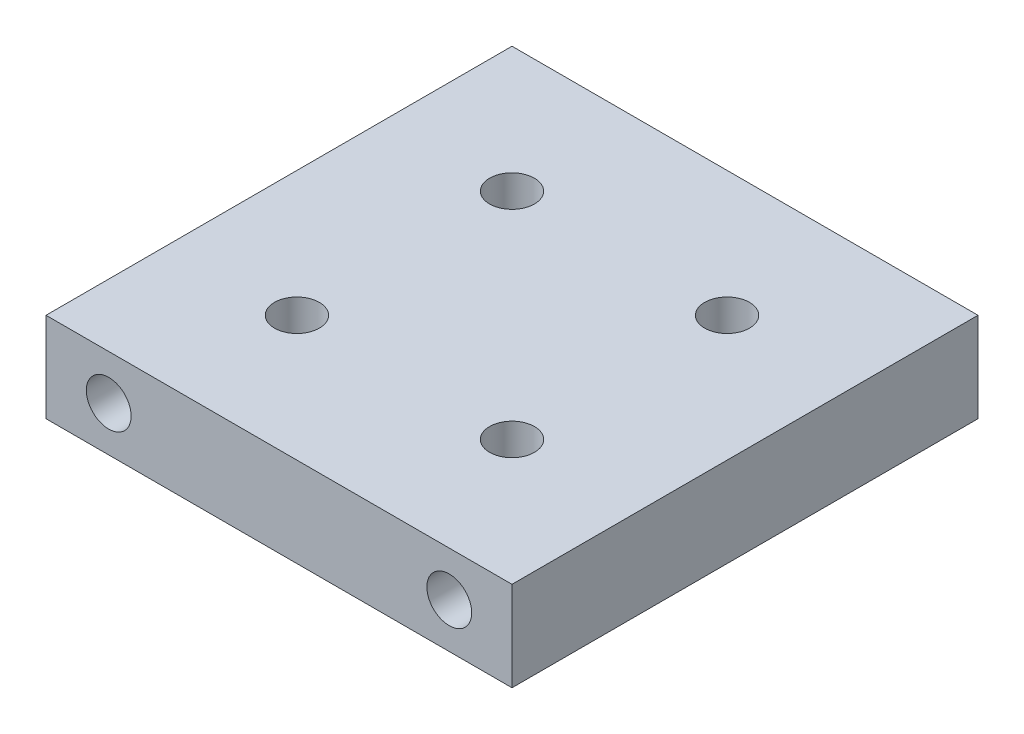
SolidWorks part; units mm, degrees
ref_plane "Front Plane" through (0, 0, 0) normal (0, 0, 1) x (1, 0, 0)
ref_plane "Top Plane" through (0, 0, 0) normal (0, 1, 0) x (1, 0, 0)
ref_plane "Right Plane" through (0, 0, 0) normal (1, 0, 0) x (0, 0, -1)
sketch "Sketch1" plane through (0, 0, 0) normal (0, 1, 0) x (1, 0, 0)
  line L1 (13, 13) -> (-13, 13)
  line L2 (13, 13) -> (13, -13)
  line L3 (13, -13) -> (-13, -13)
  line L4 (-13, 13) -> (-13, -13)
  line L5 (13, 13) -> (-13, -13) construction
  line L6 (13, -13) -> (-13, 13) construction
  circle A0 centre (-6, -6) radius 1.25
  circle A1 centre (6, -6) radius 1.25
  circle A2 centre (6, 6) radius 1.25
  circle A3 centre (-6, 6) radius 1.25
  point P0 (0, 0)
  dimension "D1" = 26
  dimension "D2" = 26
  dimension "D3" = 2
extrude "Boss-Extrude1" add sketch "Sketch1" along normal blind 5
sketch "Sketch2" plane through (0, 0, 13) normal (0, 0, 1) x (1, 0, 0)
  circle A0 centre (-9.5, 2.5) radius 1.25
  circle A1 centre (9.5, 2.5) radius 1.25
extrude "Cut-Extrude1" cut sketch "Sketch2" against normal blind 10
pattern_linear "LPattern1" count 2 spacing 16 along (0, 0, -1) of "Cut-Extrude1"
